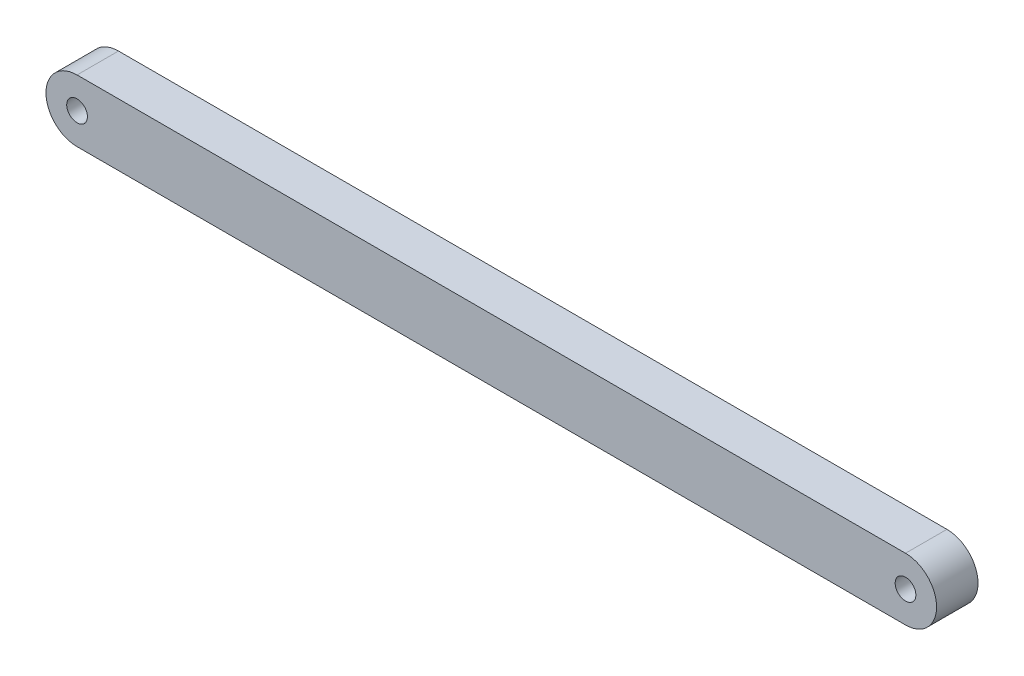
SolidWorks part; units mm, degrees
material "AISI 304"
ref_plane "前视基准面" through (0, 0, 0) normal (0, 0, 1) x (1, 0, 0)
ref_plane "上视基准面" through (0, 0, 0) normal (0, 1, 0) x (1, 0, 0)
ref_plane "右视基准面" through (0, 0, 0) normal (1, 0, 0) x (0, 0, -1)
sketch "草图1" plane through (0, 0, 0) normal (0, 0, 1) x (1, 0, 0)
  line L0 (-26.1476, 20.5151) -> (13.8524, 20.5151) construction
  line L1 (-26.1476, 22.0151) -> (13.8524, 22.0151)
  line L3 (13.8524, 19.0151) -> (-26.1476, 19.0151)
  circle A0 centre (-26.1476, 20.5151) radius 0.5
  arc A1 (-26.1476, 22.0151) -> (-26.1476, 19.0151) centre (-26.1476, 20.5151) ccw
  circle A2 centre (13.8524, 20.5151) radius 0.5
  arc A3 (13.8524, 19.0151) -> (13.8524, 22.0151) centre (13.8524, 20.5151) ccw
  dimension "D2" = 1
  dimension "D3" = 3
  dimension "D1" = 40
extrude "凸台-拉伸1" add sketch "草图1" along normal blind 2
